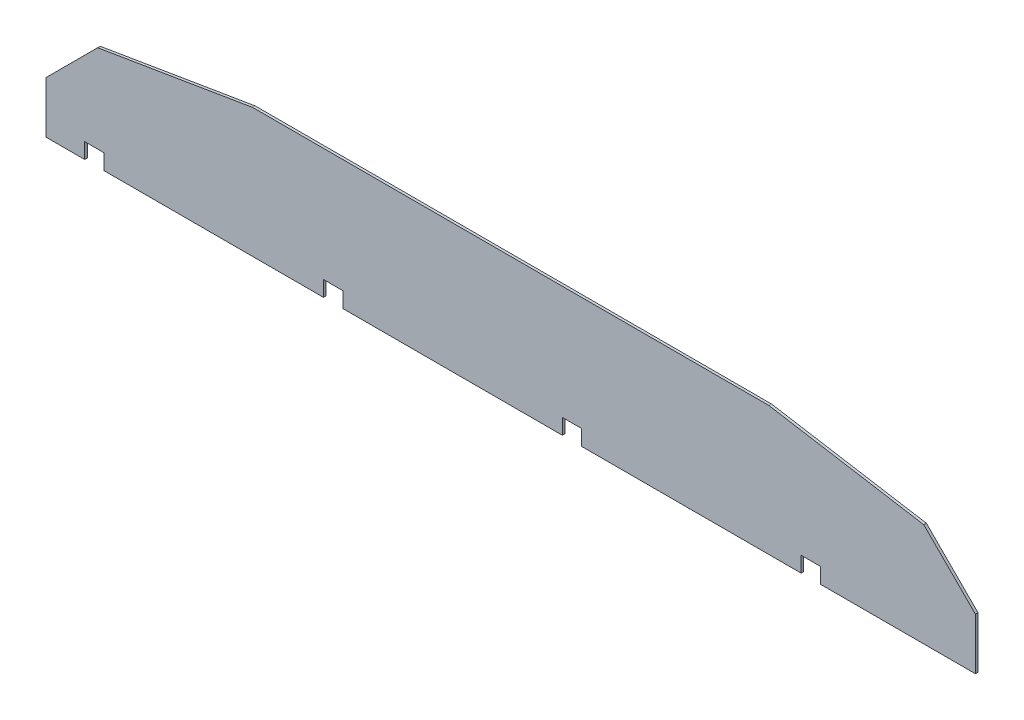
SolidWorks part; units mm, degrees
material "Märtens PU-G/2"
ref_plane "Vorne" through (0, 0, 0) normal (0, 0, 1) x (1, 0, 0)
ref_plane "Oben" through (0, 0, 0) normal (0, 1, 0) x (1, 0, 0)
ref_plane "Rechts" through (0, 0, 0) normal (1, 0, 0) x (0, 0, -1)
sketch "Skizze1" plane through (0, 0, 0) normal (0, 0, 1) x (1, 0, 0)
  line L0 (-720, 0) -> (-690, 0)
  line L1 (0, 0) -> (0, 40)
  line L2 (-160, 100) -> (-560, 100)
  line L3 (-680, 80) -> (-720, 40)
  line L4 (-720, 40) -> (-720, 0)
  line L5 (0, 40) -> (-40, 80)
  line L6 (-690, 0) -> (-690, 12)
  line L7 (-690, 12) -> (-675, 12)
  line L8 (-675, 12) -> (-675, 0)
  line L9 (-675, 0) -> (-505, 0)
  line L10 (-490, 12) -> (-490, 0)
  line L11 (-505, 12) -> (-490, 12)
  line L12 (-505, 0) -> (-505, 12)
  line L13 (-305, 12) -> (-305, 0)
  line L14 (-320, 12) -> (-305, 12)
  line L15 (-320, 0) -> (-320, 12)
  line L16 (-120, 12) -> (-120, 0)
  line L17 (-135, 12) -> (-120, 12)
  line L18 (-135, 0) -> (-135, 12)
  line L19 (-680, 80) -> (-560, 100)
  line L20 (-160, 100) -> (-40, 80)
  line L22 (-490, 0) -> (-320, 0)
  line L23 (-305, 0) -> (-135, 0)
  line L24 (-120, 0) -> (0, 0)
  point P4 (0, 100)
  point P10 (-690, 6)
  point P29 (0, 0)
  dimension "D1" = 40
  dimension "D2" = 720
  dimension "D3" = 100
  dimension "D14" = 45
  dimension "D4" = 45
  dimension "D5" = 30
  dimension "D7" = 15
  dimension "D8" = 12
  dimension "D10" = 185
  dimension "D11" = 160
  dimension "D12" = 160
  dimension "D13" = 20
  dimension "D9" = 4
extrude "Aufsatz-Linear austragen1" add sketch "Skizze1" along normal blind 2
